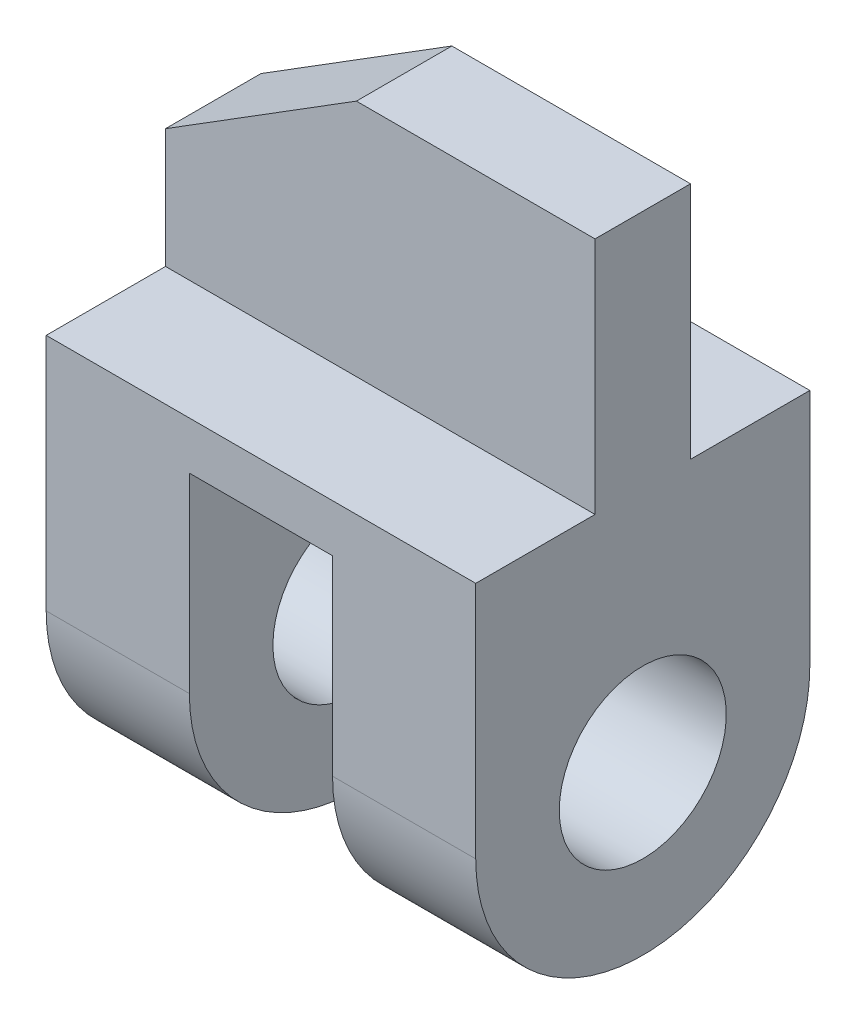
SolidWorks part; units mm, degrees
ref_plane "Front Plane" through (0, 0, 0) normal (0, 0, 1) x (1, 0, 0)
ref_plane "Top Plane" through (0, 0, 0) normal (0, 1, 0) x (1, 0, 0)
ref_plane "Right Plane" through (0, 0, 0) normal (1, 0, 0) x (0, 0, -1)
sketch "Sketch3" plane through (0, 0, 0) normal (0, 0, 1) x (1, 0, 0)
  line L0 (24.9629, 73.4564) -> (24.9629, -61.5436)
  line L1 (24.9629, 73.4564) -> (-25.0371, 73.4564)
  line L2 (24.9629, -61.5436) -> (-5.0371, -61.5436)
  line L3 (-5.0371, -61.5436) -> (-5.0371, 13.4564)
  line L4 (-5.0371, 13.4564) -> (-35.0371, 13.4564)
  line L5 (-35.0371, 13.4564) -> (-35.0371, -61.5436)
  line L6 (-35.0371, -61.5436) -> (-65.0371, -61.5436)
  line L7 (-65.0371, -61.5436) -> (-65.0371, 48.4564)
  line L8 (-65.0371, 48.4564) -> (-25.0371, 73.4564)
extrude "Boss-Extrude1" add sketch "Sketch3" along normal blind 70
sketch "Sketch4" plane through (-65.0371, 0, 0) normal (-1, 0, 0) x (0, 0, 1)
  circle A0 centre (35, -26.5436) radius 17.5
extrude "Cut-Extrude3" cut sketch "Sketch4" against normal blind 137
sketch "Sketch6" plane through (24.9629, 0, 0) normal (1, 0, 0) x (0, 0, -1)
  line L0 (-35, 73.4564) -> (-45, 73.4564)
  line L1 (-70, 73.4564) -> (0, 73.4564) construction
  line L2 (-35, 73.4564) -> (-25, 73.4564)
  line L3 (-45, 73.4564) -> (-45, 23.4564)
  line L4 (-25, 73.4564) -> (-25, 23.4564)
  line L5 (-45, 23.4564) -> (-70, 23.4564)
  line L6 (-70, -61.5436) -> (-70, 73.4564) construction
  line L7 (-25, 23.4564) -> (0, 23.4564)
  line L8 (0, -61.5436) -> (0, 73.4564) construction
  line L9 (-45, 73.4564) -> (-70, 73.4564)
  line L10 (-70, 73.4564) -> (-70, 23.4564)
  line L11 (-25, 73.4564) -> (0, 73.4564)
  line L12 (0, 73.4564) -> (0, 23.4564)
  line M9 (0, 73.4564) -> (-70, 73.4564)
  line M10 (-70, 73.4564) -> (-70, -61.5436)
extrude "Cut-Extrude4" cut sketch "Sketch6" against normal blind 137 contours L5 L3 M9 M10
sketch "Sketch7" plane through (24.9629, 0, 0) normal (1, 0, 0) x (0, 0, -1)
  line L0 (-45, 73.4564) -> (-25, 73.4564)
  line L1 (-45, 73.4564) -> (0, 73.4564) construction
  line L2 (-25, 73.4564) -> (-25, 23.4564)
  line L3 (-25, 23.4564) -> (0, 23.4564)
  line L4 (0, -61.5436) -> (0, 73.4564) construction
  line L5 (0, 23.4564) -> (0, 73.4564)
  line L6 (0, 73.4564) -> (-25, 73.4564)
  line M5 (0, -61.5436) -> (0, 73.4564)
  line M6 (0, 73.4564) -> (-45, 73.4564)
  dimension "D1" = 20
  dimension "D2" = 50
extrude "Cut-Extrude5" cut sketch "Sketch7" against normal blind 137 contours L2 L3 M5 M6
sketch "Sketch8" plane through (-65.0371, 0, 0) normal (-1, 0, 0) x (0, 0, 1)
  line L0 (35, -26.5436) -> (0, -26.5436)
  line L1 (35, -26.5436) -> (70, -26.5436)
  line L2 (0, -26.5436) -> (0, -61.5436)
  line L3 (0, 23.4564) -> (0, -61.5436) construction
  line L4 (0, -61.5436) -> (70, -61.5436)
  line L5 (70, -61.5436) -> (70, -26.5436)
  arc A0 (0, -26.5436) -> (70, -26.5436) centre (35, -26.5436) ccw
  line M8 (0, 23.4564) -> (0, -61.5436)
  line M9 (0, -61.5436) -> (70, -61.5436)
  line M10 (70, -61.5436) -> (70, 23.4564)
extrude "Cut-Extrude6" cut sketch "Sketch8" against normal blind 137 contours A0 M8 M9 | A0 L4 M10
